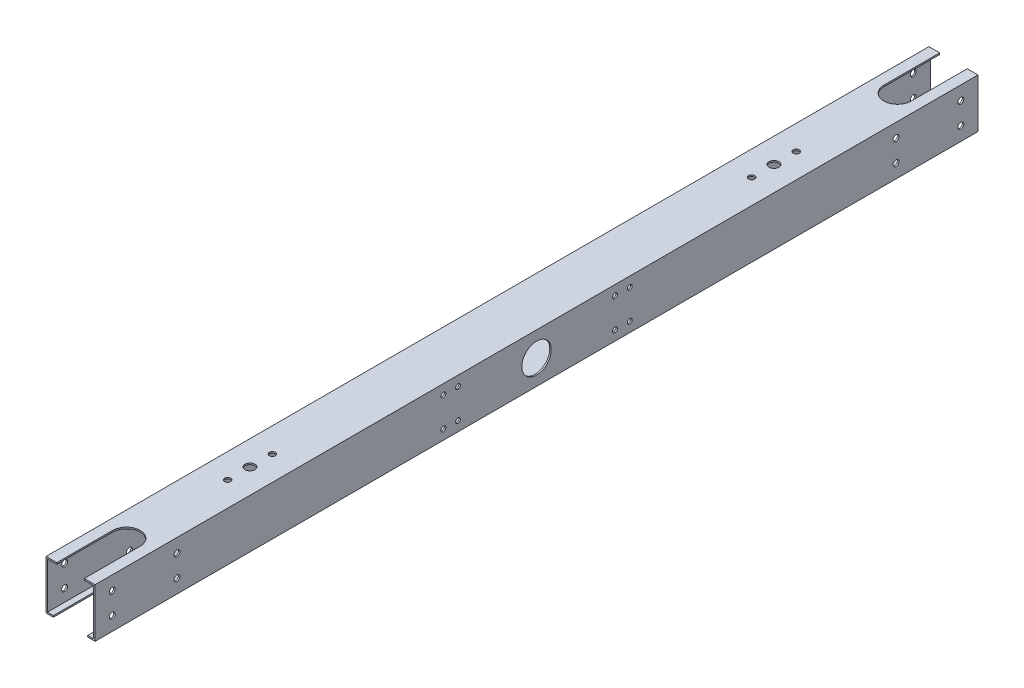
SolidWorks part; units mm, degrees
material "6061 Alloy"
ref_plane "Front Plane" through (0, 0, 0) normal (0, 0, 1) x (1, 0, 0)
ref_plane "Top Plane" through (0, 0, 0) normal (0, 1, 0) x (1, 0, 0)
ref_plane "Right Plane" through (0, 0, 0) normal (1, 0, 0) x (0, 0, -1)
sketch "Sketch1" plane through (0, 0, 0) normal (0, 0, 1) x (1, 0, 0)
  line L1 (-23.5, 23.5) -> (23.5, 23.5)
  line L2 (-23.5, 23.5) -> (-23.5, -23.5)
  line L3 (-23.5, -23.5) -> (23.5, -23.5)
  line L4 (23.5, 23.5) -> (23.5, -23.5)
  line L5 (-23.5, 23.5) -> (23.5, -23.5) construction
  line L6 (-23.5, -23.5) -> (23.5, 23.5) construction
  line L7 (-25, 25) -> (25, 25)
  line L8 (-25, 25) -> (-25, -25)
  line L9 (-25, -25) -> (25, -25)
  line L10 (25, 25) -> (25, -25)
  line L11 (-25, 25) -> (25, -25) construction
  line L12 (-25, -25) -> (25, 25) construction
  point P0 (0, 0)
  point P6 (0, 0)
  dimension "D1" = 50
  dimension "D2" = 47
  dimension "D3" = 50
  dimension "D4" = 47
extrude "Boss-Extrude1" add sketch "Sketch1" along normal blind 900
sketch "Sketch2" plane through (25, 0, 0) normal (1, 0, 0) x (0, 0, -1)
  line L1 (0, 0) -> (-900, 0) construction
  line L4 (-900, 25) -> (-900, -25) construction
  line L5 (-450, 25) -> (-450, -25) construction
  line L6 (-900, 25) -> (0, 25) construction
  line L7 (-900, -25) -> (0, -25) construction
  circle A3 centre (-450, 0) radius 15
  dimension "D1" = 30
extrude "Cut-Extrude1" cut sketch "Sketch2" against normal blind 59
sketch "Sketch3" plane through (0, 25, 0) normal (0, 1, 0) x (1, 0, 0)
  line L0 (0, -843) -> (0, -913.9861) construction
  line L5 (14, -843) -> (14, -913.9861)
  line L6 (-14, -843) -> (-14, -913.9861)
  line L7 (25, -900) -> (-25, -900) construction
  arc A0 (14, -843) -> (-14, -843) centre (0, -843) ccw
  arc A1 (-14, -913.9861) -> (14, -913.9861) centre (0, -913.9861) ccw
  point P2 (0, -878.4931)
  dimension "D2" = 14
  dimension "D1" = 57
extrude "Cut-Extrude2" cut sketch "Sketch3" against normal blind 10
sketch "Sketch4" plane through (0, -25, 0) normal (0, -1, 0) x (1, 0, 0)
  line L0 (0.0011, 850) -> (0.0011, 939.0785) construction
  line L1 (-17.4989, 850) -> (-17.4989, 939.0785)
  line L2 (17.5011, 850) -> (17.5011, 939.0785)
  line L3 (25, 900) -> (25, 0) construction
  line L4 (-25, 900) -> (25, 900) construction
  arc A0 (-17.4989, 850) -> (17.5011, 850) centre (0.0011, 850) ccw
  arc A1 (17.5011, 939.0785) -> (-17.4989, 939.0785) centre (0.0011, 939.0785) ccw
  point P2 (0.0011, 894.5393)
  dimension "D2" = 17.5
  dimension "D1" = 50
extrude "Cut-Extrude3" cut sketch "Sketch4" against normal blind 10
sketch "Sketch5" plane through (25, 0, 0) normal (1, 0, 0) x (0, 0, -1)
  line L0 (-900, -25) -> (0, -25) construction
  line L1 (-900, 25) -> (0, 25) construction
  line L2 (-900, -25) -> (-900, 25) construction
  line L3 (-849.5, 25) -> (-849.5, -25) construction
  circle A0 centre (-882.5, 11) radius 3
  circle A2 centre (-882.5, -11) radius 3
  circle A3 centre (-816.5, -11) radius 3
  circle A4 centre (-816.5, 11) radius 3
  dimension "D4" = 6
  dimension "D6" = 6
  dimension "D1" = 33
  dimension "D2" = 14
  dimension "D3" = 14
  dimension "D7" = 17.5
extrude "Cut-Extrude4" cut sketch "Sketch5" against normal blind 55
ref_plane "Plane1" through (0, 0, 450) normal (0, 0, 1) x (1, 0, 0)
mirror "Mirror1" about plane through (0, 0, 450) normal (0, 0, 1) of "Cut-Extrude4", "Cut-Extrude3", "Cut-Extrude2"
sketch "Sketch6" plane through (0, 25, 0) normal (0, 1, 0) x (1, 0, 0)
  line L0 (0, -694.2275) -> (0, -739.8525) construction
  line L2 (-27.5, -450) -> (27.5, -450) construction
  circle A0 centre (0, -694.2275) radius 3.125
  circle A1 centre (0, -739.8525) radius 3.125
  circle A2 centre (0, -717.04) radius 5
  point P8 (0, -717.04)
  dimension "D1" = 6.25
  dimension "D2" = 6.25
  dimension "D5" = 10
  dimension "D3" = 45.625
  dimension "D4" = 267.04
extrude "Cut-Extrude5" cut sketch "Sketch6" against normal blind 70
mirror "Mirror2" about plane through (0, 0, 450) normal (0, 0, 1) of "Cut-Extrude5"
sketch "Sketch7" plane through (-25, 0, 0) normal (-1, 0, 0) x (0, 0, 1)
  line L0 (450, 40.085) -> (450, -40.085) construction
  line L1 (362.5, 25) -> (362.5, -25) construction
  line L2 (900, 25) -> (0, 25) construction
  line L3 (900, -25) -> (0, -25) construction
  line L4 (349.2272, 0) -> (389.8301, 0) construction
  line L5 (375.7728, 0) -> (335.1699, 0) construction
  line L6 (524.2272, 0) -> (564.8301, 0) construction
  line L7 (550.7728, 0) -> (510.1699, 0) construction
  line L8 (537.5, 25) -> (537.5, -25) construction
  line L9 (435, 0) -> (465, 0) construction
  circle A0 centre (355, 15) radius 2.5
  circle A1 centre (370, 15) radius 2.5
  circle A2 centre (370, -15) radius 2.5
  circle A3 centre (355, -15) radius 2.5
  circle A4 centre (545, -15) radius 2.5
  circle A5 centre (530, -15) radius 2.5
  circle A6 centre (530, 15) radius 2.5
  circle A7 centre (545, 15) radius 2.5
  circle A8 centre (450, 0) radius 15 construction
  point P21 (450, 25)
  point P36 (450, 0)
  dimension "D1" = 5
  dimension "D2" = 7.5
  dimension "D3" = 15
  dimension "D4" = 87.5
extrude "Cut-Extrude6" cut sketch "Sketch7" against normal through all
